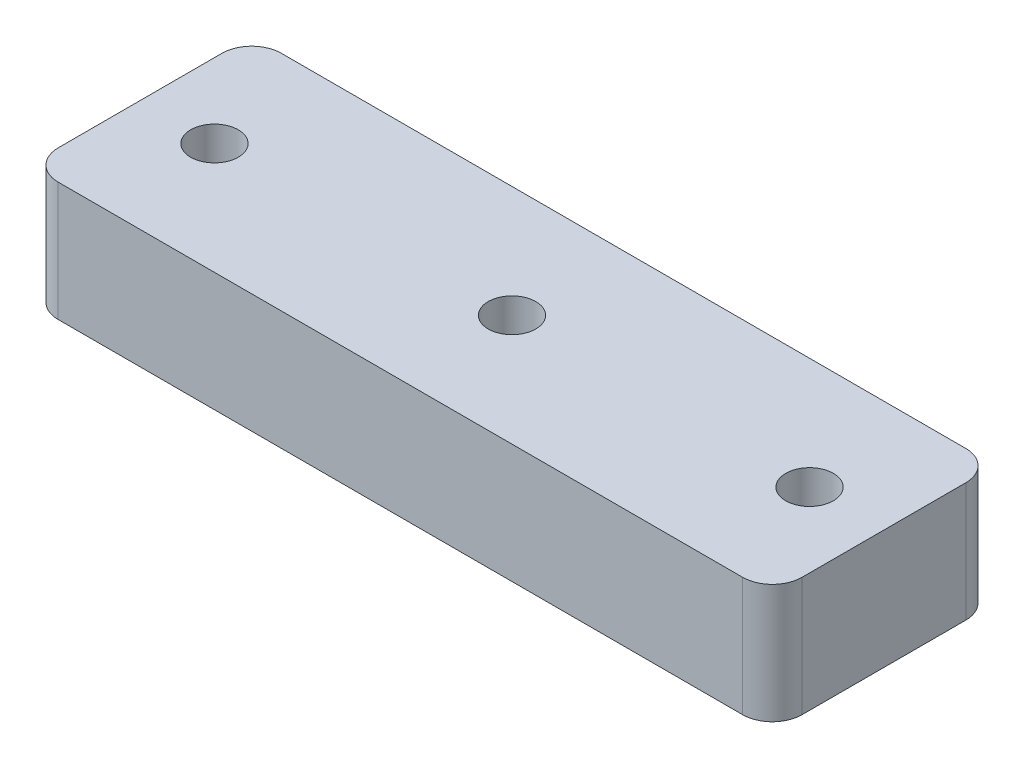
SolidWorks part; units mm, degrees
ref_plane "前视基准面" through (0, 0, 0) normal (0, 0, 1) x (1, 0, 0)
ref_plane "上视基准面" through (0, 0, 0) normal (0, 1, 0) x (1, 0, 0)
ref_plane "右视基准面" through (0, 0, 0) normal (1, 0, 0) x (0, 0, -1)
other "Configuration Table"
sketch "草图1" plane through (0, 0, 0) normal (0, 1, 0) x (1, 0, 0)
  line L0 (-25, 0) -> (25, 0) construction
  line L1 (-25, -7.5) -> (25, -7.5)
  line L2 (-25, -7.5) -> (-25, 7.5)
  line L3 (-25, 7.5) -> (25, 7.5)
  line L4 (25, -7.5) -> (25, 7.5)
  line L5 (-25, -7.5) -> (25, 7.5) construction
  line L6 (-25, 7.5) -> (25, -7.5) construction
  circle A0 centre (-20, 0) radius 1.6
  circle A1 centre (0, 0) radius 1.6
  circle A2 centre (20, 0) radius 1.6
  point P0 (0, 0)
  dimension "D3" = 3.2
  dimension "D4" = 3.2
  dimension "D5" = 3.2
  dimension "D6" = 20
  dimension "D7" = 20
  dimension "D1" = 15
  dimension "D2" = 50
extrude "凸台-拉伸1" add sketch "草图1" along normal blind 8
fillet "圆角1" radius 2 4 edges at (-25, 4, 7.5) (-25, 4, -7.5) (25, 4, -7.5) (25, 4, 7.5)
